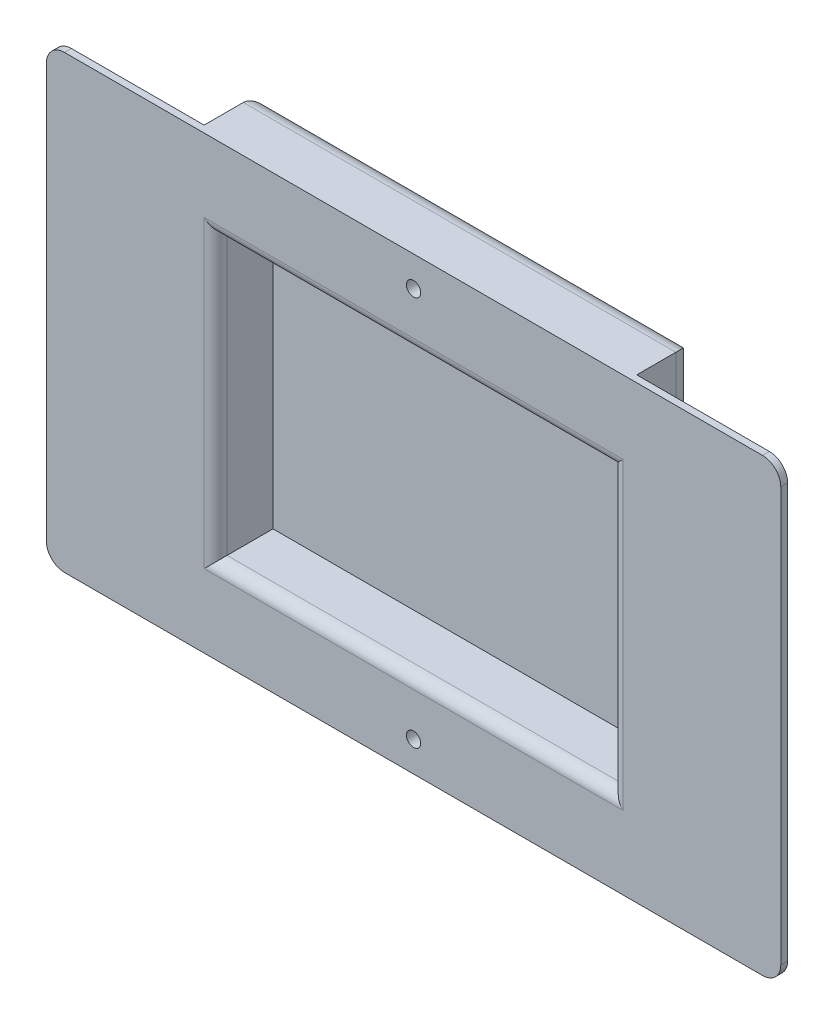
SolidWorks part; units mm, degrees
ref_plane "Front Plane" through (0, 0, 0) normal (0, 0, 1) x (1, 0, 0)
ref_plane "Top Plane" through (0, 0, 0) normal (0, 1, 0) x (1, 0, 0)
ref_plane "Right Plane" through (0, 0, 0) normal (1, 0, 0) x (0, 0, -1)
sketch "Sketch1" plane through (0, 0, 0) normal (0, 0, 1) x (1, 0, 0)
  line L1 (-64, -39.25) -> (64, -39.25)
  line L2 (-64, -39.25) -> (-64, 39.25)
  line L3 (-64, 39.25) -> (64, 39.25)
  line L4 (64, -39.25) -> (64, 39.25)
  line L5 (-64, -39.25) -> (64, 39.25) construction
  line L6 (-64, 39.25) -> (64, -39.25) construction
  point P0 (0, 0)
  dimension "D1" = 128
  dimension "D2" = 78.5
extrude "Boss-Extrude1" add sketch "Sketch1" along normal blind 11.2
sketch "Sketch2" plane through (0, 0, 11.2) normal (0, 0, 1) x (1, 0, 0)
  line L0 (0, 39.25) -> (0, -39.25) construction
  line L1 (64, 39.25) -> (-64, 39.25) construction
  line L2 (-64, -39.25) -> (64, -39.25) construction
  line L3 (-64, 0) -> (64, 0) construction
  line L4 (-64, 39.25) -> (-64, -39.25) construction
  line L5 (64, -39.25) -> (64, 39.25) construction
  line L7 (-34.5, 24.5) -> (34.5, 24.5)
  line L8 (-34.5, 24.5) -> (-34.5, -24.5)
  line L9 (-34.5, -24.5) -> (34.5, -24.5)
  line L10 (34.5, 24.5) -> (34.5, -24.5)
  line L11 (-34.5, 24.5) -> (34.5, -24.5) construction
  line L12 (-34.5, -24.5) -> (34.5, 24.5) construction
  point P12 (0, 0)
  dimension "D1" = 49
  dimension "D2" = 69
extrude "Cut-Extrude1" cut sketch "Sketch2" against normal blind 10
fillet "Fillet2" radius 2 4 edges at (-34.5, 0, 11.2) (0, -24.5, 11.2) (34.5, 0, 11.2) (0, 24.5, 11.2)
sketch "Sketch3" plane through (0, 0, 11.2) normal (0, 0, 1) x (1, 0, 0)
  line L0 (-64, 0) -> (64, 0) construction
  line L1 (-64, 39.25) -> (-64, -39.25) construction
  line L2 (64, -39.25) -> (64, 39.25) construction
  line L3 (0, 39.25) -> (0, 26.5) construction
  line L4 (64, 39.25) -> (-64, 39.25) construction
  line L5 (-36.5, 26.5) -> (36.5, 26.5) construction
  circle A0 centre (0, 34) radius 1.2446
  circle A1 centre (0, -34) radius 1.2446
  dimension "D1" = 34
extrude "Cut-Extrude2" cut sketch "Sketch3" against normal blind 10
sketch "Sketch5" plane through (0, -39.25, 0) normal (0, -1, 0) x (1, 0, 0)
  line L1 (37.7, 10) -> (64, 10)
  line L2 (37.7, 10) -> (37.7, 0)
  line L3 (37.7, 0) -> (64, 0)
  line L4 (64, 10) -> (64, 0)
  line L5 (-64, 11.2) -> (64, 11.2) construction
  line L6 (0, 11.2) -> (0, 0) construction
  line L7 (-64, 0) -> (64, 0) construction
  line L8 (-37.7, 0) -> (-64, 0)
  line L9 (-64, 10) -> (-64, 0)
  line L10 (-37.7, 10) -> (-64, 10)
  line L11 (-37.7, 10) -> (-37.7, 0)
  dimension "D1" = 1.2
extrude "Cut-Extrude3" cut sketch "Sketch5" against normal up to next
fillet "Fillet3" radius 3.175 8 edges at (0, 39.25, 0) (37.7, 0, 0) (0, -39.25, 0) (-37.7, 0, 0) (-64, -39.25, 10.6) (-64, 39.25, 10.6) (64, 39.25, 10.6) (64, -39.25, 10.6)
equation "\"Box_Width\" = 79.93mm"
equation "\"Box_Length\" = 129.93mm"
equation "\"LoggerMount_Width\" = 26.04mm"
equation "\"LoggerMount_Length\" = 45.85mm"
equation "\"LoggerMount_Hole\"= 2.5mm"
equation "\"Box_Hole\"= 4mm"
equation "\"D1@Sketch1\"=\"Lid_Length\""
equation "\"D2@Sketch1\"=\"Lid_Width\""
equation "\"Lid_Length\" = 128mm"
equation "\"Lid_Width\" = 78.5mm"
